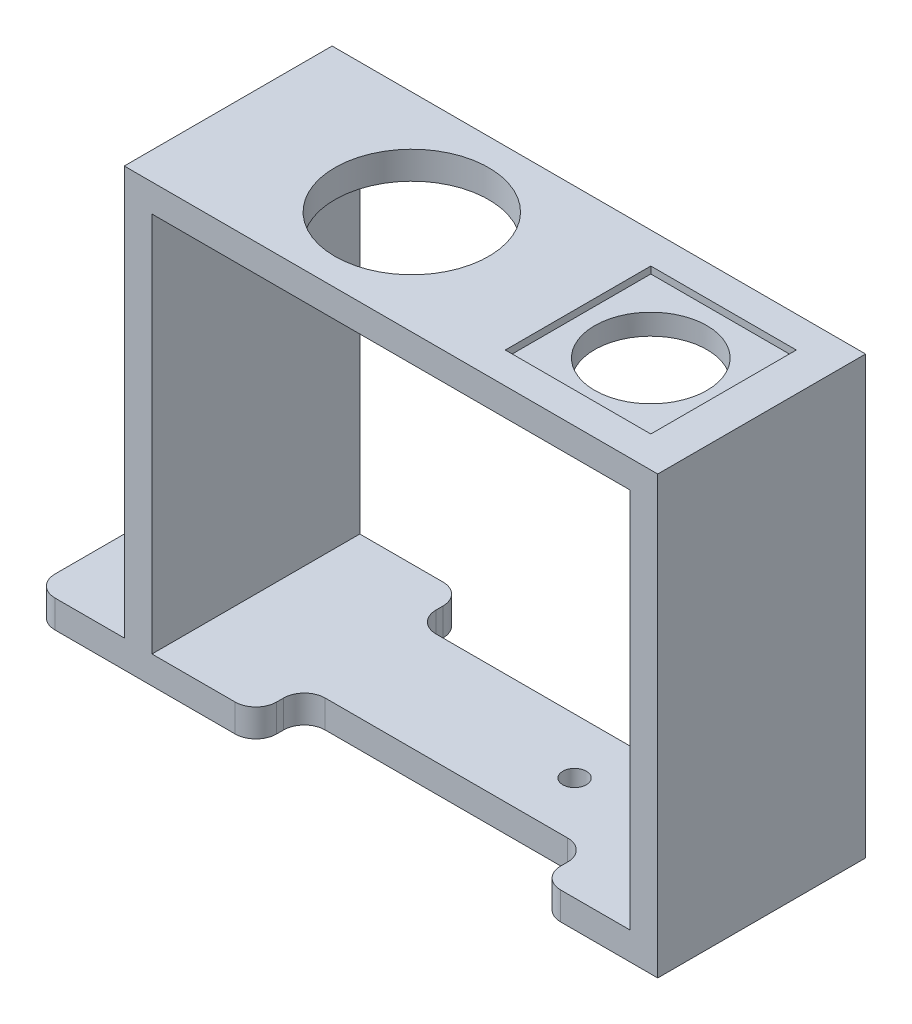
SolidWorks part; units mm, degrees
ref_plane "前视基准面" through (0, 0, 0) normal (0, 0, 1) x (1, 0, 0)
ref_plane "上视基准面" through (0, 0, 0) normal (0, 1, 0) x (1, 0, 0)
ref_plane "右视基准面" through (0, 0, 0) normal (1, 0, 0) x (0, 0, -1)
sketch "草图1" plane through (0, 0, 0) normal (0, 1, 0) x (1, 0, 0)
  line L1 (-45, -15) -> (45, -15)
  line L2 (-45, -15) -> (-45, 15)
  line L3 (-45, 15) -> (45, 15)
  line L4 (45, -15) -> (45, 15)
  line L5 (-45, -15) -> (45, 15) construction
  line L6 (-45, 15) -> (45, -15) construction
  circle A0 centre (-40, 0) radius 1.7
  point P0 (0, 0)
  dimension "D1" = 5
  dimension "D2" = 3.4
  dimension "D3" = 85
  dimension "D5" = 15
  dimension "D4" = 30
extrude "凸台-拉伸1" add sketch "草图1" along normal blind 4
sketch "草图2" plane through (0, 4, 0) normal (0, 1, 0) x (1, 0, 0)
  line L0 (45, 15) -> (-45, 15) construction
  line L1 (-32, 15) -> (-28, 15)
  line L2 (-32, 15) -> (-32, -15)
  line L3 (-32, -15) -> (-28, -15)
  line L4 (-28, 15) -> (-28, -15)
  line L5 (-32, 15) -> (-28, -15) construction
  line L6 (-32, -15) -> (-28, 15) construction
  line L7 (-45, -15) -> (45, -15) construction
  line L8 (45, -15) -> (45, 15) construction
  line L9 (45, 15) -> (41, 15)
  line L10 (45, 15) -> (45, -15)
  line L11 (45, -15) -> (41, -15)
  line L12 (41, 15) -> (41, -15)
  line L13 (45, 15) -> (41, -15) construction
  line L14 (45, -15) -> (41, 15) construction
  circle A0 centre (-40, 0) radius 1.7 construction
  point P4 (-30, 0)
  point P13 (43, 0)
  dimension "D1" = 4
  dimension "D2" = 4
  dimension "D3" = 0
  dimension "D4" = 8
extrude "凸台-拉伸2" add sketch "草图2" along normal blind 55
sketch "草图3" plane through (0, 59, 0) normal (0, 1, 0) x (1, 0, 0)
  line L0 (-28, -15) -> (41, -15) construction
  line L1 (-32, 15) -> (45, 15)
  line L2 (-32, 15) -> (-32, -15)
  line L3 (-32, -15) -> (45, -15)
  line L4 (45, 15) -> (45, -15)
  line L5 (-32, 15) -> (45, -15) construction
  line L6 (-32, -15) -> (45, 15) construction
  line L7 (45, -15) -> (45, 15) construction
  circle A0 centre (-5.5, 0) radius 11.1
  point P4 (6.5, 0)
  dimension "D1" = 22.2
  dimension "D2" = 26.5
  dimension "D3" = 0
extrude "凸台-拉伸3" add sketch "草图3" along normal blind 4
sketch "草图4" plane through (0, 63, 0) normal (0, 1, 0) x (1, 0, 0)
  line L0 (45, -15) -> (45, 15) construction
  line L2 (17, -15) -> (-28, -15) construction
  line L3 (17, -15) -> (17, 15) construction
  line L4 (17, 15) -> (-28, 15) construction
  line L5 (-28, -15) -> (-28, 15) construction
  line L6 (17, -15) -> (-28, 15) construction
  line L7 (17, 15) -> (-28, -15) construction
  circle A0 centre (29, 0) radius 8.1
  point P4 (-5.5, 0)
  dimension "D1" = 16.2
  dimension "D2" = 16
  dimension "D3" = 45
  dimension "D4" = 30
extrude "切除-拉伸1" cut sketch "草图4" against normal blind 4
sketch "草图5" plane through (0, 63, 0) normal (0, 1, 0) x (1, 0, 0)
  line L1 (18.5, -10.5) -> (39.5, -10.5)
  line L2 (18.5, -10.5) -> (18.5, 10.5)
  line L3 (18.5, 10.5) -> (39.5, 10.5)
  line L4 (39.5, -10.5) -> (39.5, 10.5)
  line L5 (18.5, -10.5) -> (39.5, 10.5) construction
  line L6 (18.5, 10.5) -> (39.5, -10.5) construction
  point P0 (29, 0)
  dimension "D1" = 21
  dimension "D2" = 21
extrude "切除-拉伸2" cut sketch "草图5" against normal blind 1
sketch "草图6" plane through (0, 4, 0) normal (0, 1, 0) x (1, 0, 0)
  line L0 (-28, -15) -> (41, -15) construction
  circle A0 centre (18, 0) radius 1.7
  circle A1 centre (-40, 0) radius 1.7 construction
  point P6 (-5.5, 0)
  dimension "D1" = 3.4
  dimension "D2" = 15
  dimension "D3" = 58
extrude "切除-拉伸3" cut sketch "草图6" against normal blind 5
sketch "草图7" plane through (0, 4, 0) normal (0, 1, 0) x (1, 0, 0)
  line L0 (-28, -15) -> (41, -15) construction
  line L1 (-13, -15) -> (28, -15)
  line L2 (-13, -15) -> (-13, -8)
  line L3 (-13, -8) -> (28, -8)
  line L4 (28, -15) -> (28, -8)
  line L5 (-13, -15) -> (28, -8) construction
  line L6 (-13, -8) -> (28, -15) construction
  line L7 (41, 15) -> (-28, 15) construction
  line L8 (28, 15) -> (-13, 15)
  line L9 (28, 15) -> (28, 8)
  line L10 (28, 8) -> (-13, 8)
  line L11 (-13, 15) -> (-13, 8)
  line L12 (28, 15) -> (-13, 8) construction
  line L13 (28, 8) -> (-13, 15) construction
  line L14 (-28, -15) -> (-28, 15) construction
  circle A0 centre (18, 0) radius 1.7 construction
  point P4 (7.5, -11.5)
  point P11 (7.5, 11.5)
  dimension "D4" = 10
  dimension "D1" = 7
  dimension "D2" = 7
  dimension "D3" = 10
  dimension "D5" = 15
  dimension "D6" = 15
extrude "切除-拉伸4" cut sketch "草图7" against normal blind 10
fillet "圆角1" radius 3 10 edges at (-45, 2, -15) (-45, 2, 15) (28, 2, 8) (28, 2, 15) (-13, 2, 15) (-13, 2, 8) (-13, 2, -15) (-13, 2, -8) (28, 2, -15) (28, 2, -8)
